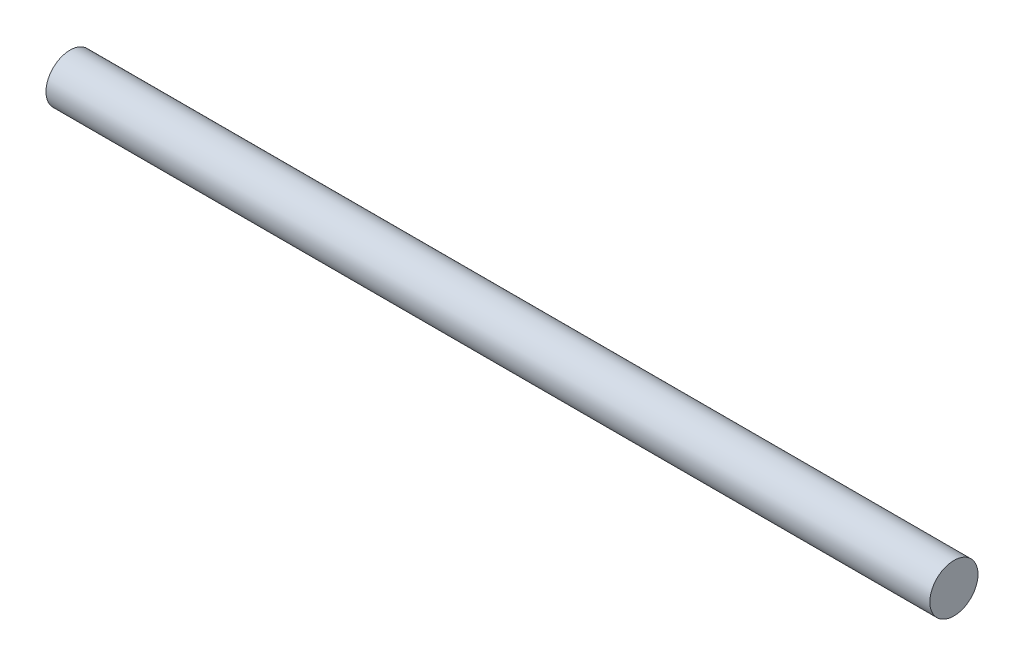
SolidWorks part; units mm, degrees
ref_plane "Front Plane" through (0, 0, 0) normal (0, 0, 1) x (1, 0, 0)
ref_plane "Top Plane" through (0, 0, 0) normal (0, 1, 0) x (1, 0, 0)
ref_plane "Right Plane" through (0, 0, 0) normal (1, 0, 0) x (0, 0, -1)
sketch "Sketch1" plane through (0, 0, 0) normal (1, 0, 0) x (0, 0, -1)
  circle A0 centre (0, 0) radius 8.89
  dimension "D1" = 17.78
extrude "Boss-Extrude1" add sketch "Sketch1" along normal blind 163.2 and the other way blind 163.2
